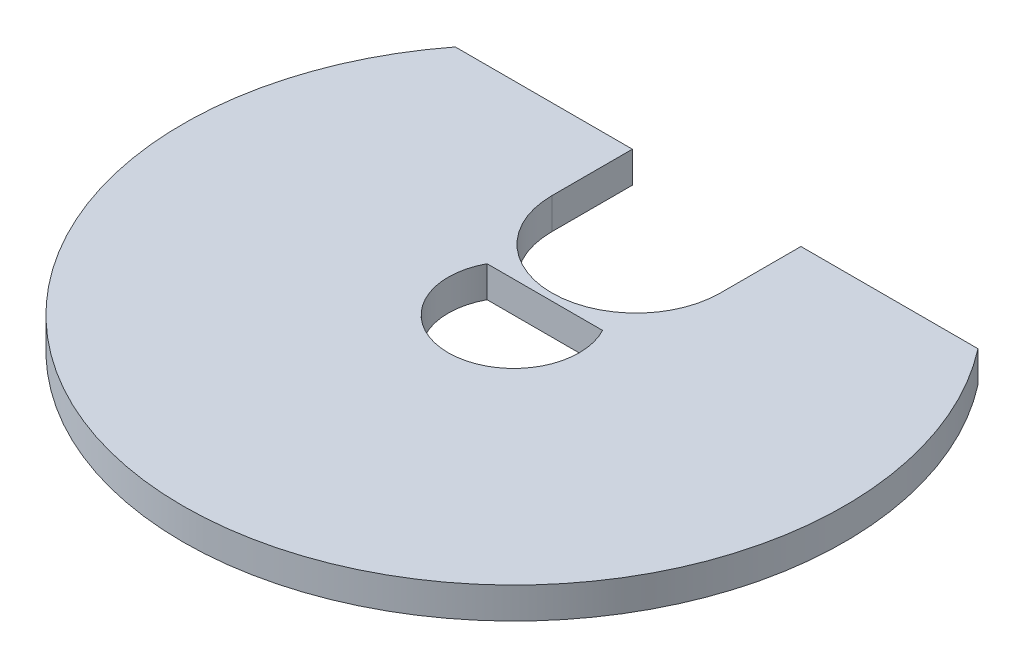
SolidWorks part; units mm, degrees
material "Alumina"
ref_plane "Front Plane" through (0, 0, 0) normal (0, 0, 1) x (1, 0, 0)
ref_plane "Top Plane" through (0, 0, 0) normal (0, 1, 0) x (1, 0, 0)
ref_plane "Right Plane" through (0, 0, 0) normal (1, 0, 0) x (0, 0, -1)
sketch "Sketch2" plane through (0, 0, 0) normal (0, 1, 0) x (1, 0, 0)
  line L0 (-53.1696, 41.275) -> (-17.145, 41.275)
  line L1 (-17.145, 41.275) -> (-17.145, 24.892)
  line L2 (17.145, 24.892) -> (17.145, 41.275)
  line L3 (17.145, 41.275) -> (53.1696, 41.275)
  arc A0 (-53.1696, 41.275) -> (53.1696, 41.275) centre (0, 0) ccw
  arc A1 (-17.145, 24.892) -> (17.145, 24.892) centre (0, 24.892) ccw
  point P9 (0, 0)
  dimension "D1" = 134.62
  dimension "D4" = 17.145
  dimension "D2" = 41.275
  dimension "D3" = 16.383
extrude "Boss-Extrude1" add sketch "Sketch2" along normal blind 6.35
sketch "Sketch3" plane through (0, 6.35, 0) normal (0, 1, 0) x (1, 0, 0)
  line L0 (-11.7475, 6.3102) -> (11.7475, 6.3102)
  arc A0 (-11.7475, 6.3102) -> (11.7475, 6.3102) centre (0, 0) ccw
  dimension "D1" = 26.67
  dimension "D2" = 23.495
extrude "Cut-Extrude1" cut sketch "Sketch3" against normal through all
